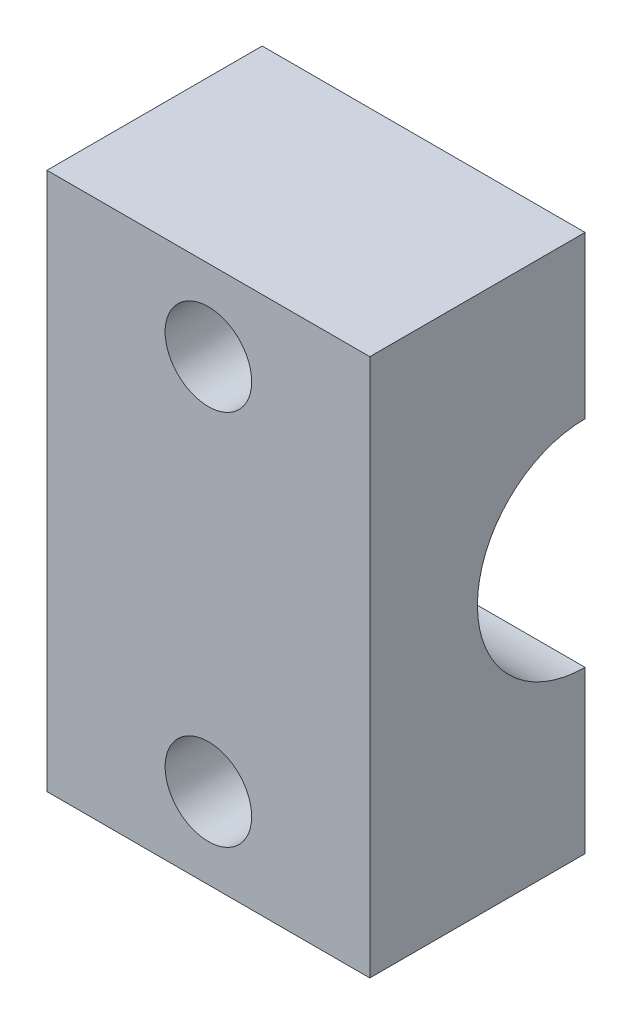
SolidWorks part; units mm, degrees
material "6061 Alloy"
ref_plane "Front Plane" through (0, 0, 0) normal (0, 0, 1) x (1, 0, 0)
ref_plane "Top Plane" through (0, 0, 0) normal (0, 1, 0) x (1, 0, 0)
ref_plane "Right Plane" through (0, 0, 0) normal (1, 0, 0) x (0, 0, -1)
sketch "Sketch1" plane through (0, 0, 0) normal (0, 0, 1) x (1, 0, 0)
  line L1 (9.525, -15.875) -> (-9.525, -15.875)
  line L2 (9.525, -15.875) -> (9.525, 15.875)
  line L3 (9.525, 15.875) -> (-9.525, 15.875)
  line L4 (-9.525, -15.875) -> (-9.525, 15.875)
  line L5 (9.525, -15.875) -> (-9.525, 15.875) construction
  line L6 (9.525, 15.875) -> (-9.525, -15.875) construction
  point P0 (0, 0)
  dimension "D1" = 31.75
  dimension "D2" = 19.05
extrude "Boss-Extrude1" add sketch "Sketch1" along normal blind 12.7
sketch "Sketch2" plane through (9.525, 0, 0) normal (1, 0, 0) x (0, 0, -1)
  circle A0 centre (0, 0) radius 6.35
  dimension "D1" = 12.7
extrude "Cut-Extrude1" cut sketch "Sketch2" against normal through all
hole_wizard "1/4-20 Tapped Hole1" positions "Sketch3" profile "Sketch4" tap size "1/4-20" standard "ANSI Inch" end condition through all
sketch "Sketch3" plane through (0, 0, 12.7) normal (0, 0, 1) x (1, 0, 0)
  line L0 (9.525, 15.875) -> (-9.525, 15.875) construction
  line L1 (-9.525, -15.875) -> (9.525, -15.875) construction
  point P0 (0, 11.1125)
  point P5 (0, -11.1125)
  dimension "D1" = 4.7625
  dimension "D2" = 4.7625
sketch "Sketch4" plane through (0, 11.1125, 12.7) normal (1, 0, 0) x (0, -1, 0)
  line L0 (0, 0) -> (0, 12.7)
  line L1 (0, 12.7) -> (2.5527, 12.7)
  line L2 (2.5527, 12.7) -> (2.5527, 0)
  line L5 (2.5527, 0) -> (0, 0)
  line L11 (0, -6.35) -> (0, 107.95) construction
  dimension "Thru Tap Drill Dia." = 5.1054
  dimension "Thru Tap Drill Depth" = 12.7
cosmetic thread "Hole Thread1" parameters "D2"=6.35
cosmetic thread "Hole Thread2" parameters "D2"=6.35
